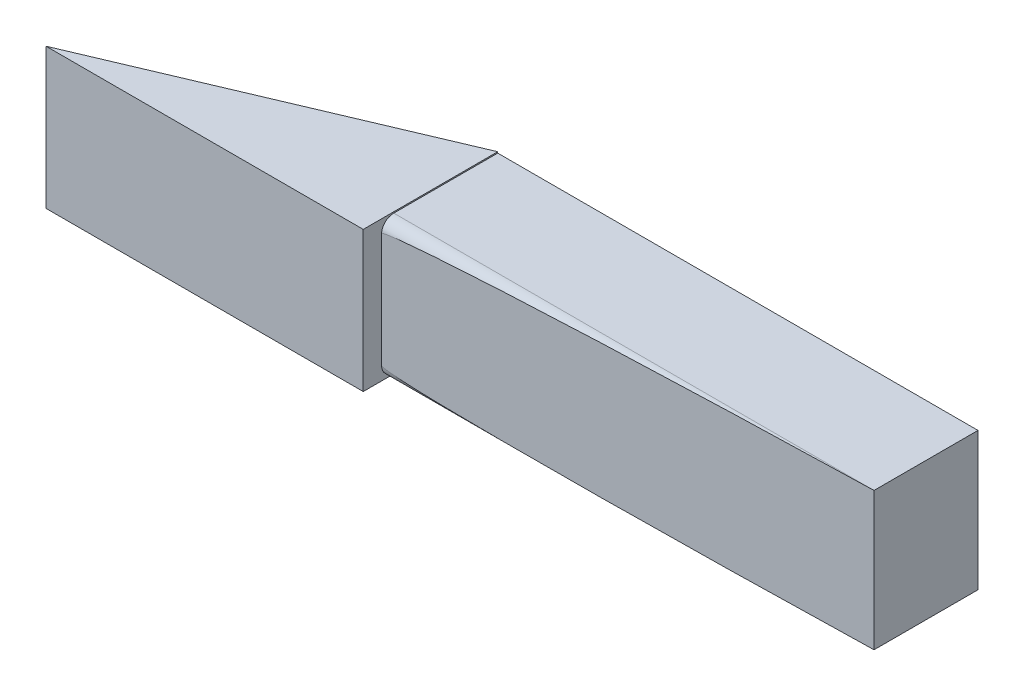
SolidWorks part; units mm, degrees
ref_plane "Plan de face" through (0, 0, 0) normal (0, 0, 1) x (1, 0, 0)
ref_plane "Plan de dessus" through (0, 0, 0) normal (0, 1, 0) x (1, 0, 0)
ref_plane "Plan de droite" through (0, 0, 0) normal (1, 0, 0) x (0, 0, -1)
sketch "Esquisse3" plane through (0, 0, 0) normal (0, 1, 0) x (1, 0, 0)
  line L0 (-209.2333, -136.9068) -> (-157.2935, -114.8878)
  line L1 (-157.2935, -131.9068) -> (-157.2935, -112.9068) construction
  line L2 (-157.2935, -114.8878) -> (-78.6663, -114.8878)
  line L3 (-78.6663, -114.8878) -> (-78.6663, -131.9068)
  line L4 (42.7065, -131.9068) -> (-157.2935, -131.9068) construction
  line L5 (-78.6663, -131.9068) -> (-157.2935, -133.9068)
  line L7 (-157.2935, -133.9068) -> (-157.2935, -136.9068)
  line L8 (-57.2935, -136.9068) -> (-209.2333, -136.9068) construction
  line L9 (-157.2935, -136.9068) -> (-209.2333, -136.9068)
extrude "Boss.-Extru.1" add sketch "Esquisse3" against normal blind 23
ref_plane "Plan1" through (-209.2333, 0, 0) normal (1, 0, 0) x (0, 1, 0)
sketch "Esquisse5" plane through (-209.2333, 0, 0) normal (1, 0, 0) x (0, 1, 0)
  line L0 (-20, 133.9068) -> (-20, 117.8878)
  line L6 (-3, 133.9068) -> (-3, 117.8878)
  line L7 (-20, 133.9068) -> (-3, 133.9068)
  line L8 (-20, 117.8878) -> (-20, 114.8878)
  line L9 (-3, 117.8878) -> (-3, 114.8878)
  line L11 (-20, 114.8878) -> (-3, 114.8878)
  point P1 (0, 114.8878)
  point P2 (-23, 114.8878)
extrude "Enlèv. mat.-Extru.2" cut sketch "Esquisse5" along normal offset from surface (47.9398 mm away) 4 up to face at (-157.2935, -11.5, 135.4068)
sketch "Esquisse6" plane through (-78.6663, 0, 0) normal (1, 0, 0) x (0, 0, -1)
  line L2 (-133.9068, -20.8) -> (-133.9068, -2)
  line L3 (-114.2464, -22.8) -> (-114.2464, -0.2)
  line L15 (-131.9068, -22.8) -> (-114.2464, -22.8)
  line L17 (-114.2464, -0.2) -> (-131.9068, -0.2)
  arc A2 (-131.9068, -0.2) -> (-133.9068, -2) centre (-131.9168, -2.2) ccw
  arc A3 (-133.9068, -20.8) -> (-131.9068, -22.8) centre (-131.9068, -20.8) ccw
extrude "Enlèv. de mat.-Extru.-Mince1" cut sketch "Esquisse6" against normal up to surface (78.6272 mm away) thin contours A3 | A2 | L17 A2 L2 A3 L15 up to face at (-157.2935, -11.5, 135.4068) thin type one direction wall 1
